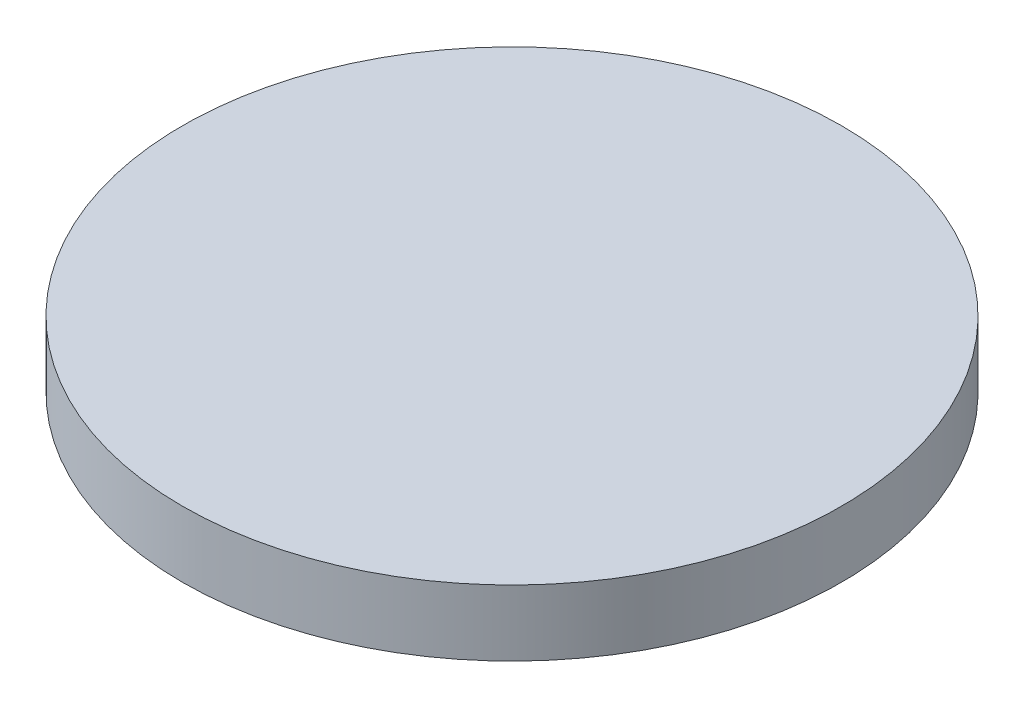
SolidWorks part; units mm, degrees
material "Nickel"
ref_plane "Front" through (0, 0, 0) normal (0, 0, 1) x (1, 0, 0)
ref_plane "Top" through (0, 0, 0) normal (0, 1, 0) x (1, 0, 0)
ref_plane "Right" through (0, 0, 0) normal (1, 0, 0) x (0, 0, -1)
sketch "Sketch1" plane through (0, 0, 0) normal (0, 1, 0) x (1, 0, 0)
  circle A0 centre (0, 0) radius 0.25
  dimension "D1" = 0.5
extrude "Boss-Extrude1" add sketch "Sketch1" along normal blind 0.05
